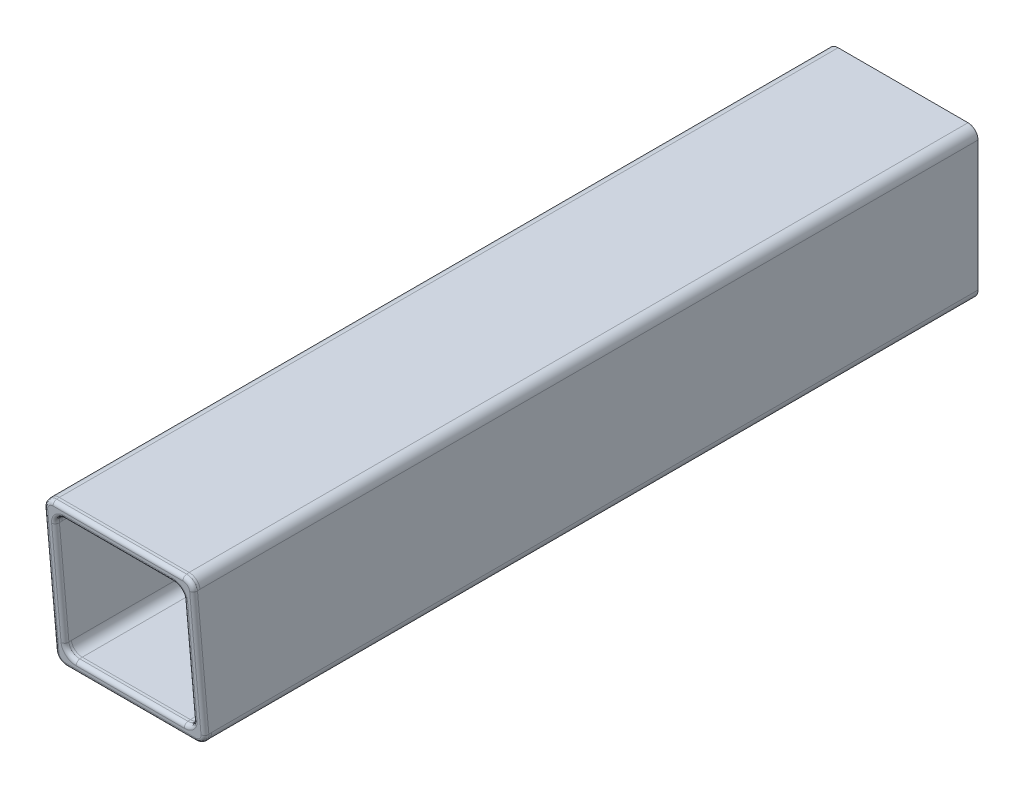
SolidWorks part; units mm, degrees
material "ASTM A500 Grade B Steel"
ref_plane "Front Plane" through (0, 0, 0) normal (0, 0, 1) x (1, 0, 0)
ref_plane "Top Plane" through (0, 0, 0) normal (0, 1, 0) x (1, 0, 0)
ref_plane "Right Plane" through (0, 0, 0) normal (1, 0, 0) x (0, 0, -1)
sketch "Sketch1" plane through (0, 0, 0) normal (0, 0, 1) x (1, 0, 0)
  line L0 (5.3086, -2.7686) -> (32.7914, -2.7686)
  line L1 (2.54, 0) -> (35.56, 0)
  line L2 (0, -2.54) -> (0, -35.56)
  line L3 (2.54, -38.1) -> (35.56, -38.1)
  line L4 (38.1, -2.54) -> (38.1, -35.56)
  line L5 (35.3314, -5.3086) -> (35.3314, -32.7914)
  line L6 (5.3086, -35.3314) -> (32.7914, -35.3314)
  line L7 (2.7686, -5.3086) -> (2.7686, -32.7914)
  line L8 (0, 0) -> (0, -38.1) construction
  line L9 (0, -38.1) -> (38.1, -38.1) construction
  line L10 (38.1, 0) -> (38.1, -38.1) construction
  line L11 (2.7686, -2.7686) -> (2.7686, -35.3314) construction
  line L12 (2.7686, -35.3314) -> (35.3314, -35.3314) construction
  line L13 (35.3314, -2.7686) -> (35.3314, -35.3314) construction
  line L14 (2.7686, -2.7686) -> (35.3314, -2.7686) construction
  line L15 (0, 0) -> (38.1, 0) construction
  arc A0 (0, -35.56) -> (2.54, -38.1) centre (2.54, -35.56) ccw
  arc A1 (38.1, -35.56) -> (35.56, -38.1) centre (35.56, -35.56) cw
  arc A2 (2.7686, -32.7914) -> (5.3086, -35.3314) centre (5.3086, -32.7914) ccw
  arc A3 (32.7914, -35.3314) -> (35.3314, -32.7914) centre (32.7914, -32.7914) ccw
  arc A4 (35.3314, -5.3086) -> (32.7914, -2.7686) centre (32.7914, -5.3086) ccw
  arc A5 (38.1, -2.54) -> (35.56, 0) centre (35.56, -2.54) ccw
  arc A6 (0, -2.54) -> (2.54, 0) centre (2.54, -2.54) cw
  arc A7 (5.3086, -2.7686) -> (2.7686, -5.3086) centre (5.3086, -5.3086) ccw
  point P12 (0, -38.1)
  dimension "D4" = 2.54
  dimension "D3" = 2.7686
extrude "Boss-Extrude1" add sketch "Sketch1" along normal blind 198
sketch "Sketch3" plane through (38.1, 0, 0) normal (1, 0, 0) x (0, 0, -1)
  line L0 (-198, 0) -> (-194.6667, -38.1)
  line L1 (-198, -38.1) -> (0, -38.1) construction
  line L2 (-194.6667, -38.1) -> (-198, -38.1)
  line L3 (-198, -38.1) -> (-198, 0)
  dimension "D1" = 5
extrude "Cut-Extrude3" cut sketch "Sketch3" against normal through all
sketch "Sketch4" plane through (0, -17.1912, 196.496) normal (0, -0.0872, 0.9962) x (1, 0, 0)
  line L0 (35.3314, 11.928) -> (35.3314, -15.6598) construction
  line L1 (32.7914, -18.2095) -> (5.3086, -18.2095) construction
  line L2 (2.7686, -15.6598) -> (2.7686, 11.928) construction
  line L3 (5.3086, 14.4777) -> (32.7914, 14.4777) construction
  line L4 (2.54, -20.9887) -> (35.56, -20.9887)
  line L5 (38.1, -18.439) -> (38.1, 14.7071)
  line L6 (35.56, 17.2568) -> (2.54, 17.2568)
  line L7 (0, 14.7071) -> (0, -18.439)
  line L8 (2.54, -20.9887) -> (35.56, -20.9887)
  line L9 (38.1, -18.439) -> (38.1, 14.7071)
  line L10 (35.56, 17.2568) -> (2.54, 17.2568)
  line L11 (0, 14.7071) -> (0, -18.439)
  line L12 (35.3314, 11.928) -> (35.3314, -15.6598)
  line L13 (32.7914, -18.2095) -> (5.3086, -18.2095)
  line L14 (2.7686, -15.6598) -> (2.7686, 11.928)
  line L15 (5.3086, 14.4777) -> (32.7914, 14.4777)
  ellipse E0 centre (32.7914, 11.928) end of major axis (32.7914, 9.3783) minor radius 2.54 (35.3314, 11.928) -> (32.7914, 14.4777) ccw construction
  ellipse E1 centre (32.7914, -15.6598) end of major axis (32.7914, -18.2095) minor radius 2.54 (32.7914, -18.2095) -> (35.3314, -15.6598) ccw construction
  ellipse E2 centre (5.3086, -15.6598) end of major axis (5.3086, -18.2095) minor radius 2.54 (2.7686, -15.6598) -> (5.3086, -18.2095) ccw construction
  ellipse E3 centre (5.3086, 11.928) end of major axis (5.3086, 9.3783) minor radius 2.54 (5.3086, 14.4777) -> (2.7686, 11.928) ccw construction
  ellipse E4 centre (35.56, -18.439) end of major axis (35.56, -20.9887) minor radius 2.54 (35.56, -20.9887) -> (38.1, -18.439) ccw
  ellipse E5 centre (35.56, 14.7071) end of major axis (35.56, 17.2568) minor radius 2.54 (38.1, 14.7071) -> (35.56, 17.2568) ccw
  ellipse E6 centre (2.54, 14.7071) end of major axis (2.54, 12.1574) minor radius 2.54 (2.54, 17.2568) -> (0, 14.7071) ccw
  ellipse E7 centre (2.54, -18.439) end of major axis (2.54, -20.9887) minor radius 2.54 (0, -18.439) -> (2.54, -20.9887) ccw
  ellipse E8 centre (35.56, -18.439) end of major axis (35.56, -20.9887) minor radius 2.54 (35.56, -20.9887) -> (38.1, -18.439) ccw
  ellipse E9 centre (35.56, 14.7071) end of major axis (35.56, 17.2568) minor radius 2.54 (38.1, 14.7071) -> (35.56, 17.2568) ccw
  ellipse E10 centre (2.54, 14.7071) end of major axis (2.54, 12.1574) minor radius 2.54 (2.54, 17.2568) -> (0, 14.7071) ccw
  ellipse E11 centre (2.54, -18.439) end of major axis (2.54, -20.9887) minor radius 2.54 (0, -18.439) -> (2.54, -20.9887) ccw
  ellipse E12 centre (32.7914, 11.928) end of major axis (32.7914, 9.3783) minor radius 2.54 (35.3314, 11.928) -> (32.7914, 14.4777) ccw
  ellipse E13 centre (32.7914, -15.6598) end of major axis (32.7914, -18.2095) minor radius 2.54 (32.7914, -18.2095) -> (35.3314, -15.6598) ccw
  ellipse E14 centre (5.3086, -15.6598) end of major axis (5.3086, -18.2095) minor radius 2.54 (2.7686, -15.6598) -> (5.3086, -18.2095) ccw
  ellipse E15 centre (5.3086, 11.928) end of major axis (5.3086, 9.3783) minor radius 2.54 (5.3086, 14.4777) -> (2.7686, 11.928) ccw
  dimension "D1" = 0
extrude "Boss-Extrude2" add sketch "Sketch4" along normal up to surface (1.6363 mm away)
fillet "Fillet1" radius 1 16 edges at (0.7439, -0.8866, 199.565) (19.05, -0.1426, 199.6301) (37.3561, -0.8866, 199.565) (38.1, -19.1926, 197.9634) (37.3561, -37.4987, 196.3619) (19.05, -38.2426, 196.2968) (0.7439, -37.4987, 196.3619) (0, -19.1926, 197.9634) (19.05, -2.9112, 199.3879) (3.5125, -3.6552, 199.3228) (2.7686, -19.1926, 197.9634) (3.5125, -34.7301, 196.6041) (19.05, -35.474, 196.539) (34.5875, -34.7301, 196.6041) (35.3314, -19.1926, 197.9634) (34.5875, -3.6552, 199.3228)
